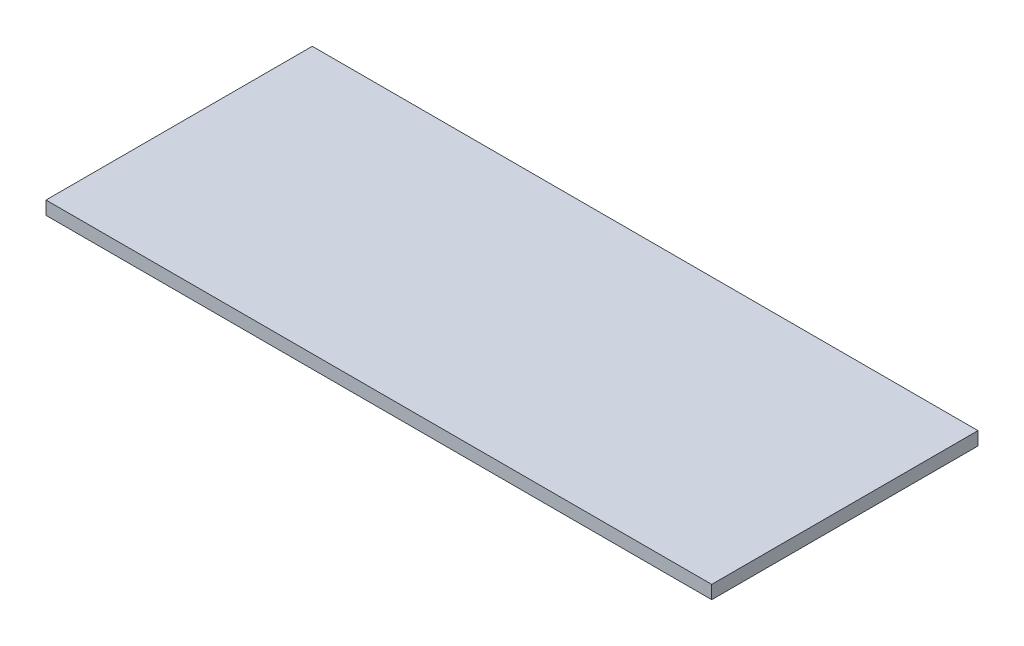
SolidWorks part; units mm, degrees
ref_plane "Front Plane" through (0, 0, 0) normal (0, 0, 1) x (1, 0, 0)
ref_plane "Top Plane" through (0, 0, 0) normal (0, 1, 0) x (1, 0, 0)
ref_plane "Right Plane" through (0, 0, 0) normal (1, 0, 0) x (0, 0, -1)
sketch "Sketch1" plane through (0, 0, 0) normal (0, 1, 0) x (1, 0, 0)
  line L1 (-1250, 500) -> (1250, 500)
  line L2 (-1250, 500) -> (-1250, -500)
  line L3 (-1250, -500) -> (1250, -500)
  line L4 (1250, 500) -> (1250, -500)
  line L5 (-1250, 500) -> (1250, -500) construction
  line L6 (-1250, -500) -> (1250, 500) construction
  point P0 (0, 0)
  dimension "D1" = 2500
  dimension "D2" = 1000
extrude "Boss-Extrude1" add sketch "Sketch1" along normal blind 50
